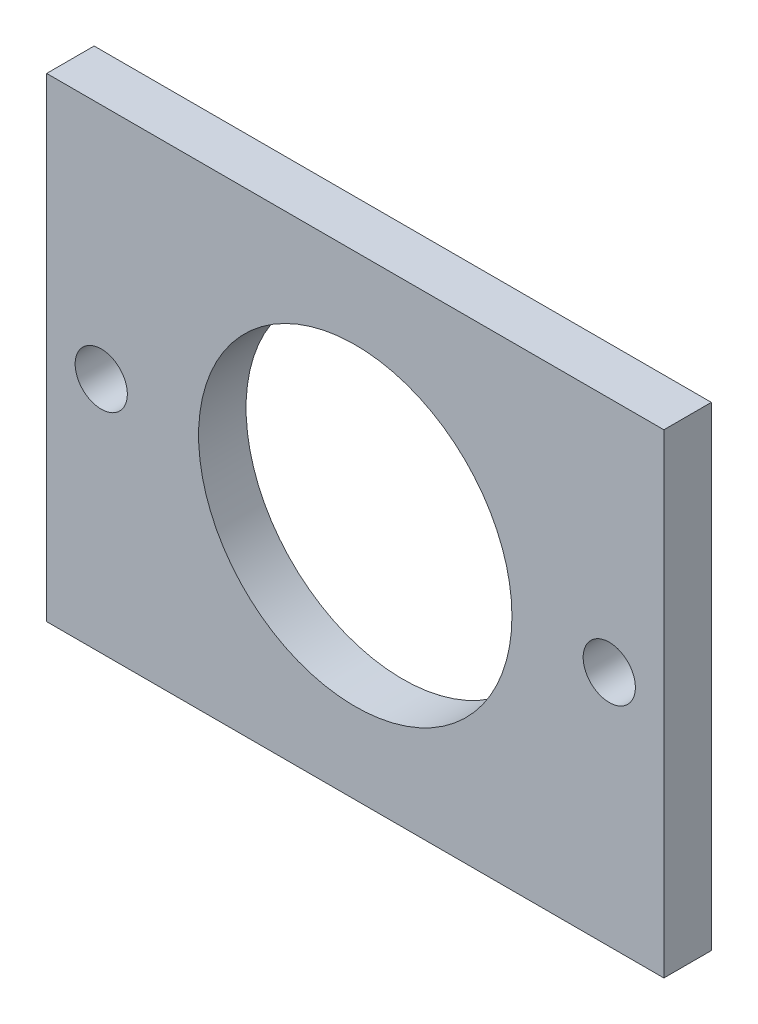
SolidWorks part; units mm, degrees
ref_plane "Front Plane" through (0, 0, 0) normal (0, 0, 1) x (1, 0, 0)
ref_plane "Top Plane" through (0, 0, 0) normal (0, 1, 0) x (1, 0, 0)
ref_plane "Right Plane" through (0, 0, 0) normal (1, 0, 0) x (0, 0, -1)
sketch "Cap_plate_26x20x2_Profile" plane through (0, 0, 0) normal (0, 0, 1) x (1, 0, 0)
  line L1 (-0.5, -10) -> (25.5, -10)
  line L2 (-0.5, -10) -> (-0.5, 10)
  line L3 (-0.5, 10) -> (25.5, 10)
  line L4 (25.5, -10) -> (25.5, 10)
  circle A0 centre (12.5, 0) radius 6.6
  circle A1 centre (1.8, 0) radius 1.1
  circle A2 centre (23.2, 0) radius 1.1
extrude "Cap_plate_26x20x2" add sketch "Cap_plate_26x20x2_Profile" along normal blind 2 from offset 7.2
